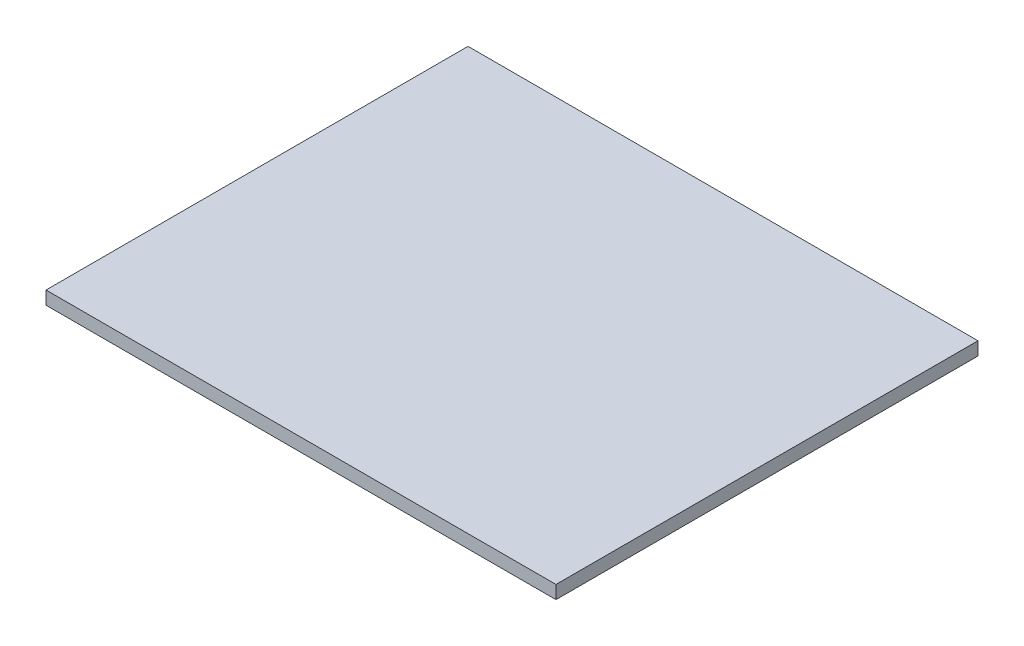
SolidWorks part; units mm, degrees
ref_plane "Front Plane" through (0, 0, 0) normal (0, 0, 1) x (1, 0, 0)
ref_plane "Top Plane" through (0, 0, 0) normal (0, 1, 0) x (1, 0, 0)
ref_plane "Right Plane" through (0, 0, 0) normal (1, 0, 0) x (0, 0, -1)
sketch "Sketch1" plane through (0, 0, 0) normal (0, 1, 0) x (1, 0, 0)
  line L1 (0, 0) -> (736.6, 0)
  line L2 (0, 0) -> (0, 609.6)
  line L3 (0, 609.6) -> (736.6, 609.6)
  line L4 (736.6, 0) -> (736.6, 609.6)
  dimension "D1" = 736.6
  dimension "D2" = 609.6
extrude "Boss-Extrude1" add sketch "Sketch1" along normal blind 19.05 contours L2 L3 L4 L1
